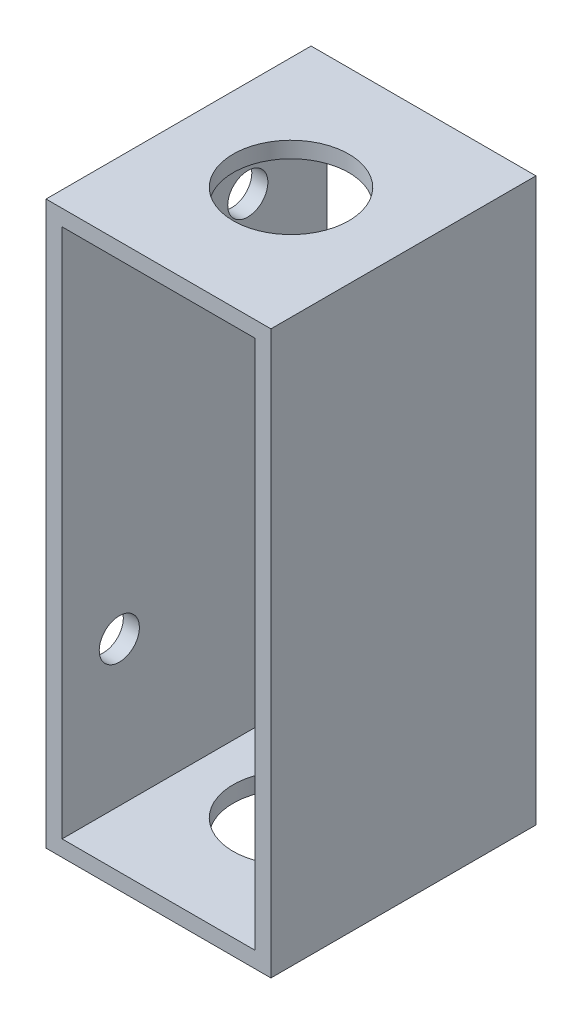
SolidWorks part; units mm, degrees
ref_plane "Front Plane" through (0, 0, 0) normal (0, 0, 1) x (1, 0, 0)
ref_plane "Top Plane" through (0, 0, 0) normal (0, 1, 0) x (1, 0, 0)
ref_plane "Right Plane" through (0, 0, 0) normal (1, 0, 0) x (0, 0, -1)
sketch "Sketch1" plane through (0, 0, 0) normal (0, 0, 1) x (1, 0, 0)
  line L1 (0, -5) -> (14, -5)
  line L2 (0, -5) -> (0, 30)
  line L3 (0, 30) -> (14, 30)
  line L4 (14, -5) -> (14, 30)
  dimension "D1" = 35
  dimension "D2" = 14
extrude "Boss-Extrude1" add sketch "Sketch1" along normal blind 16.5
sketch "Sketch3" plane through (0, 0, 0) normal (0, 0, 1) x (1, 0, 0)
  line L1 (0, 30) -> (14, 30)
  line L2 (0, 30) -> (0, -5)
  line L3 (0, -5) -> (14, -5)
  line L4 (14, 30) -> (14, -5)
  line L8 (1, 29) -> (13, 29)
  line L9 (13, 29) -> (13, -4)
  line L10 (1, -4) -> (13, -4)
  line L11 (1, 29) -> (1, -4)
  dimension "D1" = 1
extrude "Cut-Extrude3" cut sketch "Sketch3" against normal through all and the other way through all flip side to cut
sketch "Sketch4" plane through (0, 0, 0) normal (0, 1, 0) x (1, 0, 0)
  line L0 (0, -16.5) -> (14, 0) construction
  line L1 (0, 0) -> (7, -8.25) construction
  circle A0 centre (7, -8.25) radius 3.6
  point P7 (0, 0)
  dimension "D1" = 7.2
extrude "Cut-Extrude4" cut sketch "Sketch4" along direction (0, -1, 0) on the side against the normal blind 40.5 and the other way through all
sketch "Sketch5" plane through (0, 0, 0) normal (1, 0, 0) x (0, 0, -1)
  line L0 (-16.5, 30) -> (0, 30) construction
  circle A0 centre (-4.9397, 25) radius 1.25
  circle A1 centre (-12.9397, 5) radius 1.25
  dimension "D4" = 2.5
  dimension "D5" = 2.5
  dimension "D1" = 5
  dimension "D2" = 8
  dimension "D3" = 20
extrude "Cut-Extrude6" cut sketch "Sketch5" along direction (-1, 0, 0) on the side of the normal up to surface (1 mm away)
ref_plane "Plane1" through (13, 29, 16.5) normal (-1, 0, 0) x (0, 0, 1)
